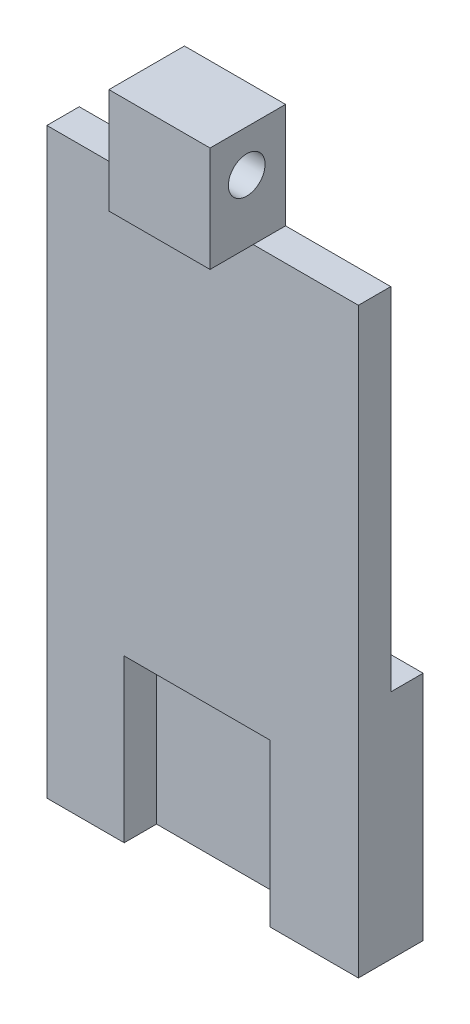
SolidWorks part; units mm, degrees
ref_plane "Front Plane" through (0, 0, 0) normal (0, 0, 1) x (1, 0, 0)
ref_plane "Top Plane" through (0, 0, 0) normal (0, 1, 0) x (1, 0, 0)
ref_plane "Right Plane" through (0, 0, 0) normal (1, 0, 0) x (0, 0, -1)
sketch "Sketch1" plane through (0, 0, 0) normal (0, 0, 1) x (1, 0, 0)
  line L0 (-4.6867, 8.4256) -> (-14.4367, 8.4256)
  line L1 (-4.6867, 18.1756) -> (4.6867, 18.1756)
  line L5 (4.6867, 8.4256) -> (4.6867, 18.1756)
  line L6 (-4.6867, 18.1756) -> (-4.6867, 8.4256)
  line L7 (-14.4367, 8.4256) -> (-14.4367, -30.5744)
  line L10 (14.4367, -30.5744) -> (14.4367, 8.4256)
  line L11 (14.4367, 8.4256) -> (4.6867, 8.4256)
  line L12 (-14.4367, -30.5744) -> (-14.4367, -45.5744)
  line L13 (-14.4367, -45.5744) -> (-7.2701, -45.5744)
  line L14 (-7.2701, -45.5744) -> (-7.2701, -30.5744)
  line L15 (-7.2701, -30.5744) -> (6.2499, -30.5744)
  line L16 (6.2499, -30.5744) -> (6.2499, -45.5744)
  line L17 (6.2499, -45.5744) -> (14.4367, -45.5744)
  line L18 (14.4367, -45.5744) -> (14.4367, -30.5744)
  point P0 (0, 0)
  point P16 (-0.5101, -30.5744)
  dimension "D1" = 9.3733
  dimension "D2" = 9.75
  dimension "D3" = 9.75
  dimension "D4" = 9.75
  dimension "D5" = 39
  dimension "D6" = 15
  dimension "D7" = 6.76
extrude "Boss-Extrude1" add sketch "Sketch1" along normal blind 3
sketch "Sketch3" plane through (0, 0, 3) normal (0, 0, 1) x (1, 0, 0)
  line L1 (-4.6867, 18.1756) -> (4.6867, 18.1756)
  line L2 (-4.6867, 18.1756) -> (-4.6867, 8.4256)
  line L3 (-4.6867, 8.4256) -> (4.6867, 8.4256)
  line L4 (4.6867, 18.1756) -> (4.6867, 8.4256)
extrude "Boss-Extrude2" add sketch "Sketch3" along normal blind 4
sketch "Sketch5" plane through (0, 0, 0) normal (0, 0, 1) x (1, 0, 0)
  line L0 (-14.4367, 8.4256) -> (-14.4367, -45.5744) construction
  line L1 (-14.4367, -24.1093) -> (14.4367, -24.1093)
  line L2 (-14.4367, -24.1093) -> (-14.4367, -45.5744)
  line L3 (-14.4367, -45.5744) -> (14.4367, -45.5744)
  line L4 (14.4367, -24.1093) -> (14.4367, -45.5744)
extrude "Boss-Extrude3" add sketch "Sketch5" against normal blind 3
sketch "Sketch6" plane through (-4.6867, 0, 0) normal (-1, 0, 0) x (0, 0, 1)
  line L0 (0, 18.1756) -> (0, 8.4256) construction
  line L1 (7, 18.1756) -> (0, 18.1756) construction
  circle A0 centre (3.6, 14.3156) radius 1.7
  dimension "D1" = 3.6
  dimension "D2" = 3.86
  dimension "D3" = 3.4
extrude "Cut-Extrude1" cut sketch "Sketch6" against normal blind 10
